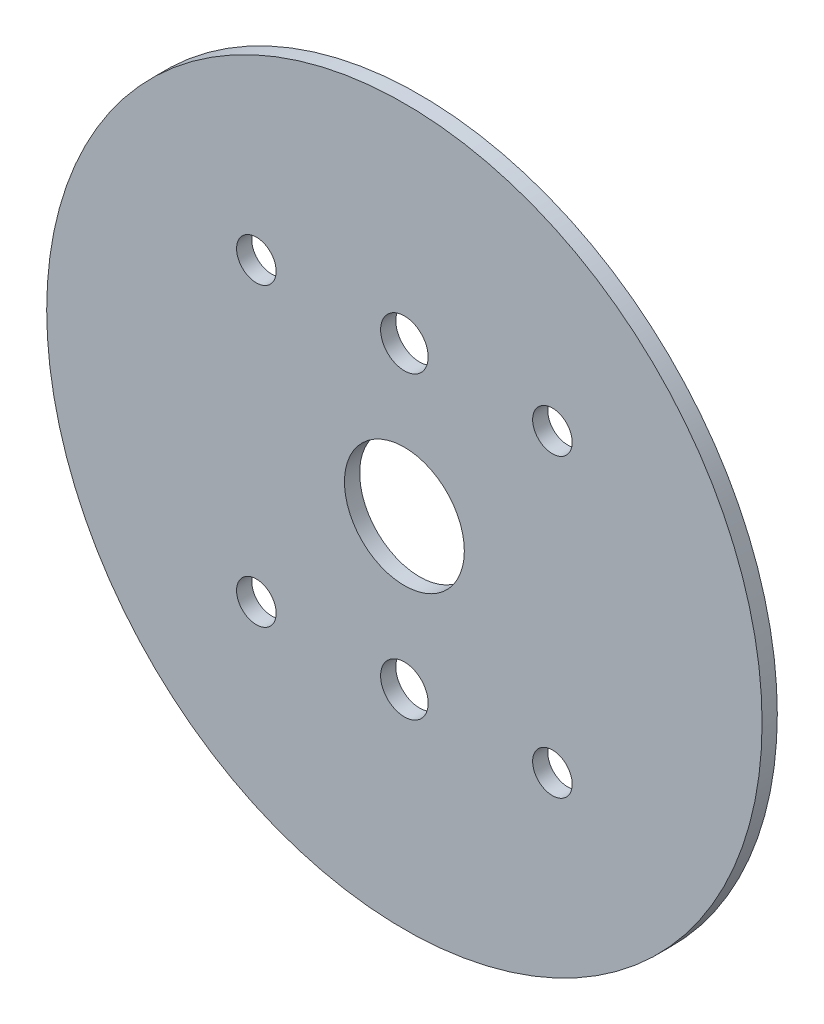
SolidWorks part; units mm, degrees
ref_plane "Front Plane" through (0, 0, 0) normal (0, 0, 1) x (1, 0, 0)
ref_plane "Top Plane" through (0, 0, 0) normal (0, 1, 0) x (1, 0, 0)
ref_plane "Right Plane" through (0, 0, 0) normal (1, 0, 0) x (0, 0, -1)
sketch "Sketch1" plane through (0, 0, 0) normal (0, 0, 1) x (1, 0, 0)
  circle A0 centre (0, 10) radius 1.5875
  circle A1 centre (0, 0) radius 23.87
  circle A2 centre (9.8783, -9.8783) radius 1.3208
  circle A3 centre (9.8783, 9.8783) radius 1.3208
  circle A4 centre (-9.8783, -9.8783) radius 1.3208
  circle A5 centre (-9.8783, 9.8783) radius 1.3208
  circle A6 centre (0, 0) radius 4
  circle A8 centre (0, -10) radius 1.5875
  circle A10 centre (-10, 0) radius 1.5875 [skipped]
  circle A11 centre (10, 0) radius 1.5875 [skipped]
  dimension "D1" = 4
  dimension "D2" = 4
extrude "Boss-Extrude2" add sketch "Sketch1" along normal blind 1.016
